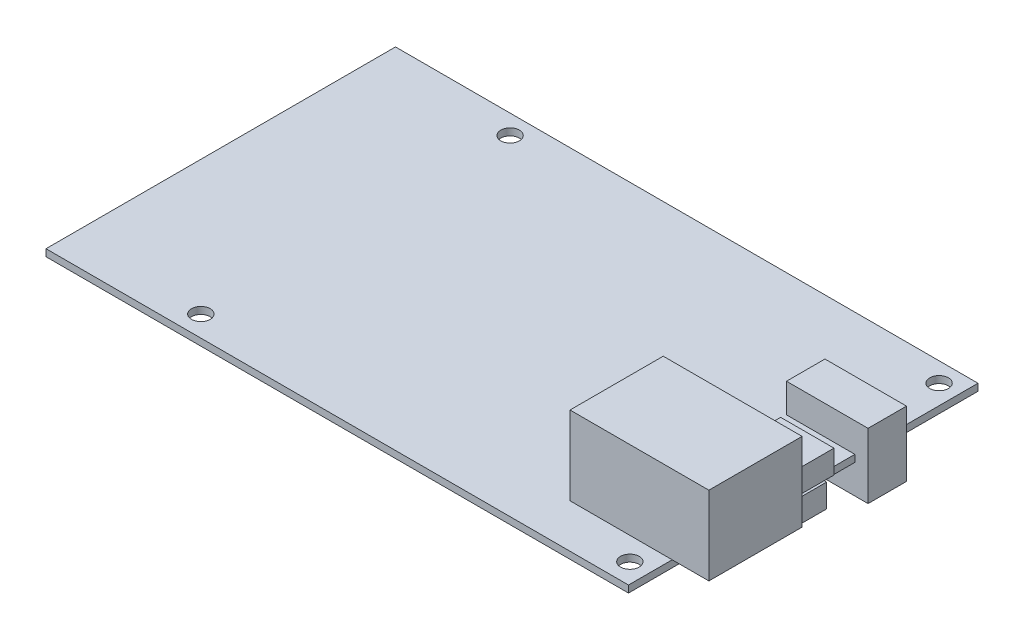
SolidWorks part; units mm, degrees
ref_plane "Plan de face" through (0, 0, 0) normal (0, 0, 1) x (1, 0, 0)
ref_plane "Plan de dessus" through (0, 0, 0) normal (0, 1, 0) x (1, 0, 0)
ref_plane "Plan de droite" through (0, 0, 0) normal (1, 0, 0) x (0, 0, -1)
sketch "Esquisse1" plane through (0, 0, 0) normal (0, 1, 0) x (1, 0, 0)
  line L1 (-100, 60) -> (0, 60)
  line L2 (-100, 60) -> (-100, 0)
  line L3 (-100, 0) -> (0, 0)
  line L4 (0, 60) -> (0, 0)
  dimension "D1" = 100
  dimension "D2" = 60
extrude "Boss.-Extru.1" add sketch "Esquisse1" against normal blind 1.2
sketch "Esquisse2" plane through (0, 0, 0) normal (0, 1, 0) x (1, 0, 0)
  line L0 (-100, 0) -> (0, 0) construction
  line L1 (-17.54, 7.5) -> (4.3, 7.5)
  line L2 (-17.54, 7.5) -> (-17.54, 23.5)
  line L3 (-17.54, 23.5) -> (4.3, 23.5)
  line L4 (4.3, 7.5) -> (4.3, 23.5)
  line L13 (0, 0) -> (0, 60) construction
  dimension "D1" = 7.5
  dimension "D2" = 16
  dimension "D3" = 21.84
  dimension "D4" = 4.3
extrude "Boss.-Extru.2" add sketch "Esquisse2" along normal blind 13.5
sketch "Esquisse3" plane through (0, 0, 0) normal (0, 1, 0) x (1, 0, 0)
  line L0 (0, 23.5) -> (0, 60) construction
  line L1 (-7.87, 33.99) -> (1.29, 33.99)
  line L2 (-7.87, 33.99) -> (-7.87, 26.37)
  line L3 (-7.87, 26.37) -> (1.29, 26.37)
  line L4 (1.29, 33.99) -> (1.29, 26.37)
  line L5 (-100, 0) -> (0, 0) construction
  dimension "D1" = 9.16
  dimension "D2" = 7.62
  dimension "D3" = 1.29
  dimension "D4" = 26.37
extrude "Boss.-Extru.3" add sketch "Esquisse3" along normal blind 4
sketch "Esquisse4" plane through (0, 0, 0) normal (0, 1, 0) x (1, 0, 0)
  line L0 (0, 33.99) -> (0, 60) construction
  line L1 (-11.736, 45.46) -> (2.264, 45.46)
  line L2 (-11.736, 45.46) -> (-11.736, 38.86)
  line L3 (-11.736, 38.86) -> (2.264, 38.86)
  line L4 (2.264, 45.46) -> (2.264, 38.86)
  line L5 (-100, 0) -> (0, 0) construction
  dimension "D1" = 14
  dimension "D2" = 6.6
  dimension "D3" = 2.264
  dimension "D4" = 38.86
extrude "Boss.-Extru.4" add sketch "Esquisse4" along normal blind 5 and the other way blind 6.2
sketch "Esquisse5" plane through (0, -1.2, 0) normal (0, -1, 0) x (1, 0, 0)
  line L0 (0, 0) -> (0, -38.86) construction
  line L1 (-3.75, -26.51) -> (0.5, -26.51)
  line L2 (-3.75, -26.51) -> (-3.75, -33.51)
  line L3 (-3.75, -33.51) -> (0.5, -33.51)
  line L4 (0.5, -26.51) -> (0.5, -33.51)
  line L5 (-100, 0) -> (0, 0) construction
  dimension "D1" = 4.25
  dimension "D2" = 0.5
  dimension "D3" = 7
  dimension "D4" = 26.51
extrude "Boss.-Extru.5" add sketch "Esquisse5" along normal blind 4
sketch "Esquisse6" plane through (0, 0, 0) normal (0, 1, 0) x (1, 0, 0)
  line L0 (-100, 0) -> (0, 0) construction
  line L1 (0, 0) -> (0, 7.5) construction
  line L2 (0, 45.46) -> (0, 60) construction
  line L4 (0, 60) -> (-100, 60) construction
  circle A0 centre (-77, 56.673) radius 1.6
  circle A1 centre (-77, 3.581) radius 1.6
  circle A2 centre (-3.35, 56.673) radius 1.6
  circle A3 centre (-3.349, 3.581) radius 1.6
  dimension "D1" = 3.2
  dimension "D2" = 3.2
  dimension "D3" = 3.2
  dimension "D4" = 3.2
  dimension "D5" = 3.581
  dimension "D6" = 3.581
  dimension "D7" = 3.349
  dimension "D8" = 77
  dimension "D9" = 3.35
  dimension "D10" = 3.327
  dimension "D11" = 77
  dimension "D12" = 3.327
extrude "Enlèv. mat.-Extru.1" cut sketch "Esquisse6" against normal up to next
sketch "Esquisse7" plane through (4.3, 0, 0) normal (1, 0, 0) x (0, 0, -1)
  line L1 (7.5, 13.5) -> (23.5, 13.5)
  line L2 (7.5, 13.5) -> (7.5, 0)
  line L3 (7.5, 0) -> (23.5, 0)
  line L4 (23.5, 13.5) -> (23.5, 0)
extrude "Boss.-Extru.6" add sketch "Esquisse7" along normal blind 2
